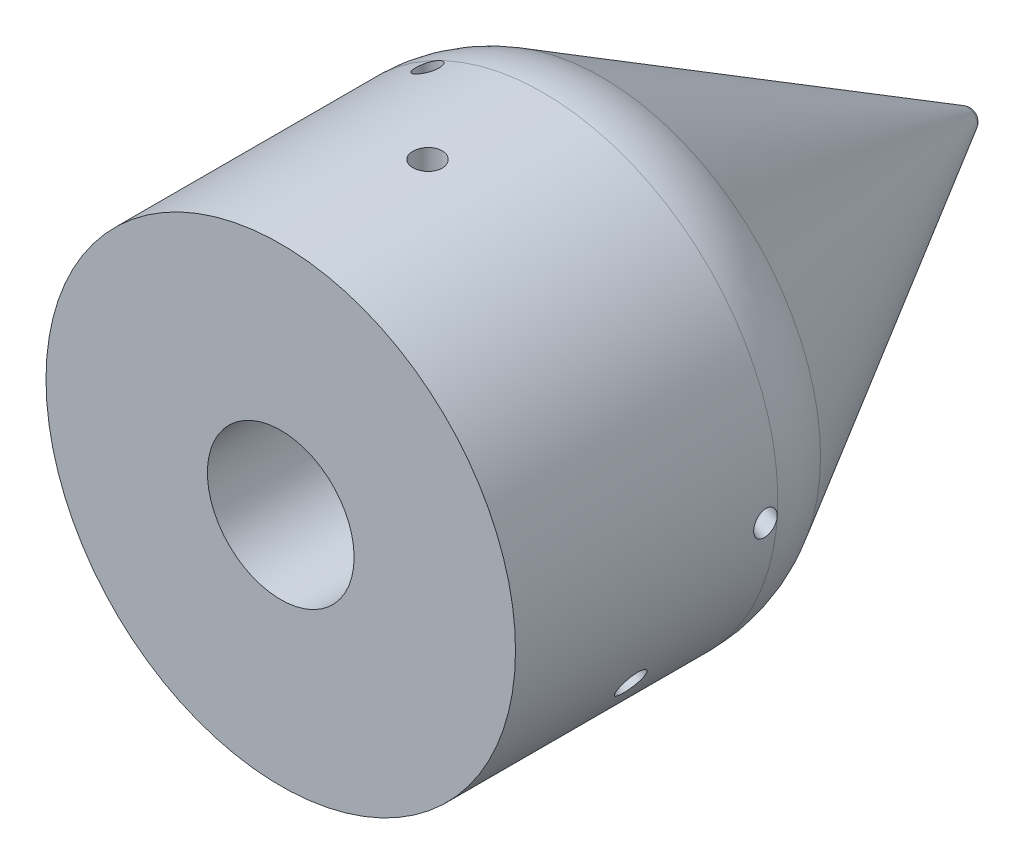
SolidWorks part; units mm, degrees
ref_plane "Alzado" through (0, 0, 0) normal (0, 0, 1) x (1, 0, 0)
ref_plane "Planta" through (0, 0, 0) normal (0, 1, 0) x (1, 0, 0)
ref_plane "Vista lateral" through (0, 0, 0) normal (1, 0, 0) x (0, 0, -1)
sketch "Croquis1" plane through (0, 0, 0) normal (0, 0, 1) x (1, 0, 0)
  circle A0 centre (0, 0) radius 12.5
  circle A1 centre (0, 0) radius 40
extrude "Saliente-Extruir1" add sketch "Croquis1" along normal blind 50
ref_plane "Plano1" through (0, 40, 0) normal (0, 1, 0) x (1, 0, 0)
ref_plane "Plano2" through (-34.641, -20, 0) normal (-0.866, -0.5, 0) x (0, 0, -1)
ref_plane "Plano3" through (34.641, -20, 0) normal (0.866, -0.5, 0) x (0, 0, -1)
sketch "Croquis2" plane through (34.641, -20, 0) normal (0.866, -0.5, 0) x (0, 0, -1)
  circle A1 centre (-25, 0) radius 2.5
extrude "Cortar-Extruir1" cut sketch "Croquis2" against normal blind 20
sketch "Croquis3" plane through (0, 40, 0) normal (0, 1, 0) x (1, 0, 0)
  circle A0 centre (0, -25) radius 2.5
extrude "Cortar-Extruir2" cut sketch "Croquis3" against normal blind 20 contours A0
sketch "Croquis4" plane through (-34.641, -20, 0) normal (-0.866, -0.5, 0) x (0, 0, -1)
  circle A0 centre (-25, 0) radius 2.5
extrude "Cortar-Extruir3" cut sketch "Croquis4" against normal blind 20
sketch "Croquis5" plane through (-34.641, -20, 0) normal (-0.866, -0.5, 0) x (0, 0, -1)
  circle A0 centre (-7.3223, 17.6777) radius 2
extrude "Cortar-Extruir4" cut sketch "Croquis5" against normal blind 20
sketch "Croquis6" plane through (34.641, -20, 0) normal (0.866, -0.5, 0) x (0, 0, -1)
  circle A0 centre (-7.3223, 17.6777) radius 2
extrude "Cortar-Extruir5" cut sketch "Croquis6" against normal blind 20
sketch "Croquis7" plane through (0, 40, 0) normal (0, 1, 0) x (1, 0, 0)
  circle A0 centre (-17.6777, -7.3223) radius 2
extrude "Cortar-Extruir6" cut sketch "Croquis7" against normal blind 20
sketch "Croquis8" plane through (0, 0, 0) normal (0, 1, 0) x (1, 0, 0)
  line L0 (0, 0) -> (40, 0)
  line L1 (40, 0) -> (-40, 0) construction
  line L2 (0, 0) -> (0, 64.0154)
  line L3 (1.7231, 66.9846) -> (40, 0)
  line L6 (0, 67.9846) -> (0, 64.0154)
  arc A0 (1.7231, 66.9846) -> (0, 67.9846) centre (0, 66) ccw
revolve "Revolución1" add sketch "Croquis8" angle 360 about L2
fillet "Redondeo1" radius 20 1 edges at (40, 0, 0)
